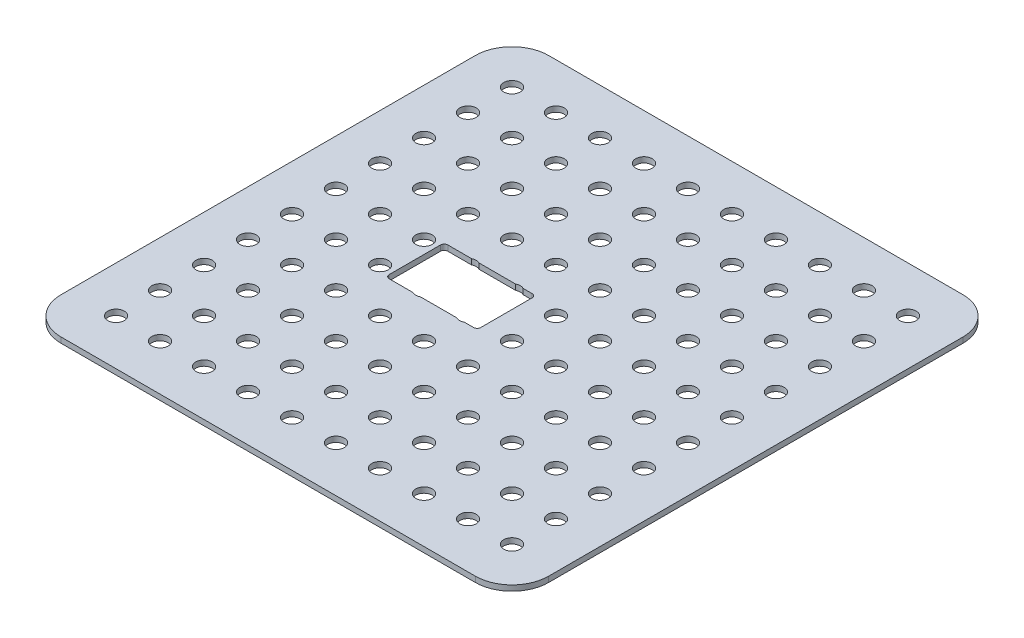
SolidWorks part; units mm, degrees
material "ABS"
ref_plane "Front Plane" through (0, 0, 0) normal (0, 0, 1) x (1, 0, 0)
ref_plane "Top Plane" through (0, 0, 0) normal (0, 1, 0) x (1, 0, 0)
ref_plane "Right Plane" through (0, 0, 0) normal (1, 0, 0) x (0, 0, -1)
sketch "SK_1" plane through (0, 0, 0) normal (0, 1, 0) x (1, 0, 0)
  line L0 (-172, -108) -> (-148, -108) construction
  line L1 (-177, -133) -> (49, -133)
  line L2 (-197, -113) -> (-197, 113)
  line L3 (-177, 133) -> (49, 133)
  line L4 (69, -113) -> (69, 113)
  line L5 (-197, -133) -> (69, 133) construction
  line L6 (-197, 133) -> (69, -133) construction
  line L7 (-172, -108) -> (-172, -84) construction
  arc A0 (49, -133) -> (69, -113) centre (49, -113) ccw
  arc A1 (-197, 113) -> (-177, 133) centre (-177, 113) cw
  arc A2 (-177, -133) -> (-197, -113) centre (-177, -113) cw
  arc A3 (49, 133) -> (69, 113) centre (49, 113) cw
  circle A4 centre (-172, -108) radius 4.5
  circle A5 centre (-148, -108) radius 4.5
  circle A6 centre (-124, -108) radius 4.5
  circle A7 centre (-100, -108) radius 4.5
  circle A8 centre (-76, -108) radius 4.5
  circle A9 centre (-52, -108) radius 4.5
  circle A10 centre (-28, -108) radius 4.5
  circle A11 centre (-4, -108) radius 4.5
  circle A12 centre (20, -108) radius 4.5
  circle A13 centre (44, -108) radius 4.5
  circle A14 centre (-148, -84) radius 4.5
  circle A15 centre (-124, -84) radius 4.5
  circle A16 centre (-100, -84) radius 4.5
  circle A17 centre (-76, -84) radius 4.5
  circle A18 centre (-52, -84) radius 4.5
  circle A19 centre (-28, -84) radius 4.5
  circle A20 centre (-4, -84) radius 4.5
  circle A21 centre (20, -84) radius 4.5
  circle A22 centre (44, -84) radius 4.5
  circle A23 centre (-148, -60) radius 4.5
  circle A24 centre (-124, -60) radius 4.5
  circle A25 centre (-100, -60) radius 4.5
  circle A26 centre (-76, -60) radius 4.5
  circle A27 centre (-52, -60) radius 4.5
  circle A28 centre (-28, -60) radius 4.5
  circle A29 centre (-4, -60) radius 4.5
  circle A30 centre (20, -60) radius 4.5
  circle A31 centre (44, -60) radius 4.5
  circle A32 centre (-148, -36) radius 4.5
  circle A33 centre (-124, -36) radius 4.5
  circle A34 centre (-100, -36) radius 4.5
  circle A35 centre (-76, -36) radius 4.5
  circle A36 centre (-52, -36) radius 4.5
  circle A37 centre (-28, -36) radius 4.5
  circle A38 centre (-4, -36) radius 4.5
  circle A39 centre (20, -36) radius 4.5
  circle A40 centre (44, -36) radius 4.5
  circle A41 centre (-148, -12) radius 4.5
  circle A42 centre (-124, -12) radius 4.5
  circle A43 centre (-100, -12) radius 4.5
  circle A44 centre (-76, -12) radius 4.5
  circle A45 centre (-52, -12) radius 4.5
  circle A46 centre (-28, -12) radius 4.5
  circle A47 centre (-4, -12) radius 4.5
  circle A48 centre (20, -12) radius 4.5
  circle A49 centre (44, -12) radius 4.5
  circle A50 centre (-148, 12) radius 4.5
  circle A51 centre (-124, 12) radius 4.5
  circle A52 centre (-100, 12) radius 4.5
  circle A53 centre (-76, 12) radius 4.5
  circle A54 centre (-52, 12) radius 4.5
  circle A55 centre (-28, 12) radius 4.5
  circle A56 centre (-4, 12) radius 4.5
  circle A57 centre (20, 12) radius 4.5
  circle A58 centre (44, 12) radius 4.5
  circle A59 centre (-148, 36) radius 4.5
  circle A60 centre (-124, 36) radius 4.5
  circle A61 centre (-100, 36) radius 4.5
  circle A62 centre (-76, 36) radius 4.5
  circle A63 centre (-52, 36) radius 4.5
  circle A64 centre (-28, 36) radius 4.5
  circle A65 centre (-4, 36) radius 4.5
  circle A66 centre (20, 36) radius 4.5
  circle A67 centre (44, 36) radius 4.5
  circle A68 centre (-148, 60) radius 4.5
  circle A69 centre (-124, 60) radius 4.5
  circle A70 centre (-100, 60) radius 4.5
  circle A71 centre (-76, 60) radius 4.5
  circle A72 centre (-52, 60) radius 4.5
  circle A73 centre (-28, 60) radius 4.5
  circle A74 centre (-4, 60) radius 4.5
  circle A75 centre (20, 60) radius 4.5
  circle A76 centre (44, 60) radius 4.5
  circle A77 centre (-148, 84) radius 4.5
  circle A78 centre (-124, 84) radius 4.5
  circle A79 centre (-100, 84) radius 4.5
  circle A80 centre (-76, 84) radius 4.5
  circle A81 centre (-52, 84) radius 4.5
  circle A82 centre (-28, 84) radius 4.5
  circle A83 centre (-4, 84) radius 4.5
  circle A84 centre (20, 84) radius 4.5
  circle A85 centre (44, 84) radius 4.5
  circle A86 centre (-148, 108) radius 4.5
  circle A87 centre (-124, 108) radius 4.5
  circle A88 centre (-100, 108) radius 4.5
  circle A89 centre (-76, 108) radius 4.5
  circle A90 centre (-52, 108) radius 4.5
  circle A91 centre (-28, 108) radius 4.5
  circle A92 centre (-4, 108) radius 4.5
  circle A93 centre (20, 108) radius 4.5
  circle A94 centre (44, 108) radius 4.5
  circle A95 centre (-172, -84) radius 4.5
  circle A96 centre (-172, -60) radius 4.5
  circle A97 centre (-172, -36) radius 4.5
  circle A98 centre (-172, -12) radius 4.5
  circle A99 centre (-172, 12) radius 4.5
  circle A100 centre (-172, 36) radius 4.5
  circle A101 centre (-172, 60) radius 4.5
  circle A102 centre (-172, 84) radius 4.5
  circle A103 centre (-172, 108) radius 4.5
  point P0 (-64, 0)
  dimension "D1" = 20
  dimension "Dia1" = 9
  dimension "W1" = 266
  dimension "H1" = 266
  dimension "X1" = 197
  dimension "Y1" = 133
  dimension "X2" = 172
  dimension "Y2" = 108
  dimension "D4" = 24
  dimension "D5" = 24
  dimension "D2" = 10
  dimension "D3" = 10
extrude "Waffle_Plate" add sketch "SK_1" along normal blind 3
sketch "SK_2" plane through (0, 0, 0) normal (0, 1, 0) x (1, 0, 0)
  line L1 (-115, -16) -> (-69, -16)
  line L2 (-117, -14) -> (-117, 14)
  line L3 (-115, 16) -> (-69, 16)
  line L4 (-67, -14) -> (-67, 14)
  line L5 (-117, -16) -> (-67, 16) construction
  line L6 (-117, 16) -> (-67, -16) construction
  arc A0 (-69, -16) -> (-67, -14) centre (-69, -14) ccw
  arc A1 (-117, 14) -> (-115, 16) centre (-115, 14) cw
  arc A2 (-115, -16) -> (-117, -14) centre (-115, -14) cw
  arc A3 (-69, 16) -> (-67, 14) centre (-69, 14) cw
  point P0 (-92, 0)
  dimension "W1" = 50
  dimension "H1" = 32
  dimension "X1" = 117
  dimension "Y1" = 16
extrude "Arm_Cutout" cut sketch "SK_2" against normal through all and the other way through all
equation "\"Plate_L\" = 266 'plate length along x"
equation "\"Plate_W\" = 266 'plate width along y"
equation "\"Plate_X\" = -64 'plate centre x in base_link"
equation "\"Plate_R\" = 20 'corner radius"
equation "\"Plate_T\" = 3 'plate thickness"
equation "\"Hole_D\" = 9 'waffle hole diameter"
equation "\"Hole_P\" = 24 'waffle hole pitch"
equation "\"Hole_N\" = 10 'holes per row / column"
equation "\"W1@SK_1\" = \"Plate_L\""
equation "\"H1@SK_1\" = \"Plate_W\""
equation "\"X1@SK_1\" = -((\"Plate_X\")-(\"Plate_L\")/2)"
equation "\"Y1@SK_1\" = -((0)-(\"Plate_W\")/2)"
equation "\"Dia1@SK_1\" = \"Hole_D\""
equation "\"X2@SK_1\" = -(\"Plate_X\" - (\"Hole_N\" - 1)*\"Hole_P\"/2)"
equation "\"Y2@SK_1\" = -(-(\"Hole_N\" - 1)*\"Hole_P\"/2)"
equation "\"D1@SK_1\" = \"Plate_R\""
equation "\"D4@SK_1\" = \"Hole_P\""
equation "\"D5@SK_1\" = \"Hole_P\""
equation "\"D2@SK_1\" = \"Hole_N\""
equation "\"D3@SK_1\" = \"Hole_N\""
equation "\"D1@Waffle_Plate\" = (\"Plate_T\")-(0)"
equation "\"Arm_X\" = -92 'OpenMANIPULATOR link1 x in base_link"
equation "\"Cut_L\" = 50 'joint-1 DYNAMIXEL cut-out length"
equation "\"Cut_W\" = 32 'joint-1 DYNAMIXEL cut-out width"
equation "\"W1@SK_2\" = \"Cut_L\""
equation "\"H1@SK_2\" = \"Cut_W\""
equation "\"X1@SK_2\" = -((\"Arm_X\")-(\"Cut_L\")/2)"
equation "\"Y1@SK_2\" = -((0)-(\"Cut_W\")/2)"
